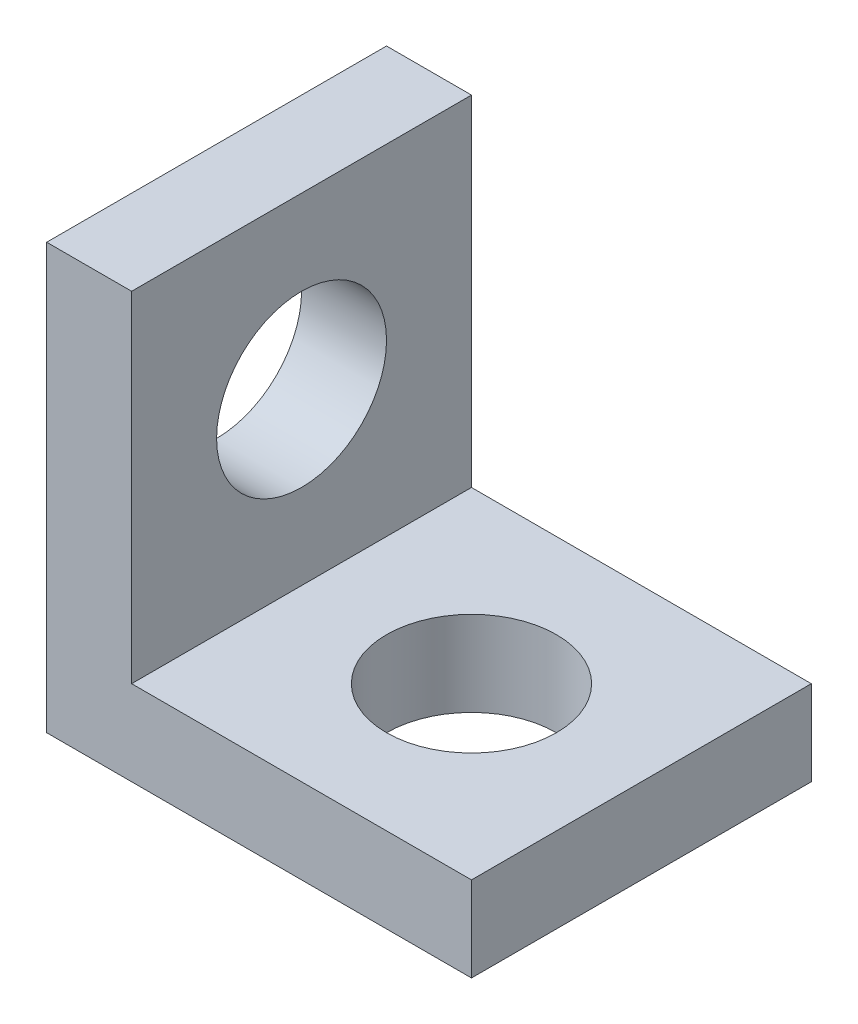
SolidWorks part; units mm, degrees
ref_plane "Front Plane" through (0, 0, 0) normal (0, 0, 1) x (1, 0, 0)
ref_plane "Top Plane" through (0, 0, 0) normal (0, 1, 0) x (1, 0, 0)
ref_plane "Right Plane" through (0, 0, 0) normal (1, 0, 0) x (0, 0, -1)
sketch "Sketch1" plane through (0, 0, 0) normal (0, 0, 1) x (1, 0, 0)
  line L0 (-30.7621, 2.921) -> (-30.7621, -12.954)
  line L1 (-30.7621, -12.954) -> (-14.8871, -12.954)
  line L2 (-14.8871, -12.954) -> (-14.8871, -9.779)
  line L3 (-14.8871, -9.779) -> (-27.5871, -9.779)
  line L4 (-27.5871, -9.779) -> (-27.5871, 2.921)
  line L5 (-27.5871, 2.921) -> (-30.7621, 2.921)
  dimension "D1" = 3.175
  dimension "D2" = 3.175
  dimension "D3" = 12.7
  dimension "D4" = 12.7
extrude "Boss-Extrude1" add sketch "Sketch1" along normal blind 12.7
sketch "Sketch2" plane through (-27.5871, 0, 0) normal (1, 0, 0) x (0, 0, -1)
  line L0 (0, -9.779) -> (0, 2.921) construction
  line L1 (-12.7, 2.921) -> (0, 2.921) construction
  circle A0 centre (-6.35, -3.429) radius 3.175
  dimension "D1" = 6.35
  dimension "D2" = 6.35
extrude "Cut-Extrude1" cut sketch "Sketch2" against normal blind 12.7
sketch "Sketch3" plane through (0, -9.779, 0) normal (0, 1, 0) x (1, 0, 0)
  line L0 (-14.8871, -12.7) -> (-14.8871, 0) construction
  line L1 (-14.8871, 0) -> (-27.5871, 0) construction
  circle A0 centre (-21.2371, -6.35) radius 3.175
  dimension "D1" = 6.35
  dimension "D2" = 6.35
extrude "Cut-Extrude2" cut sketch "Sketch3" against normal blind 12.7
